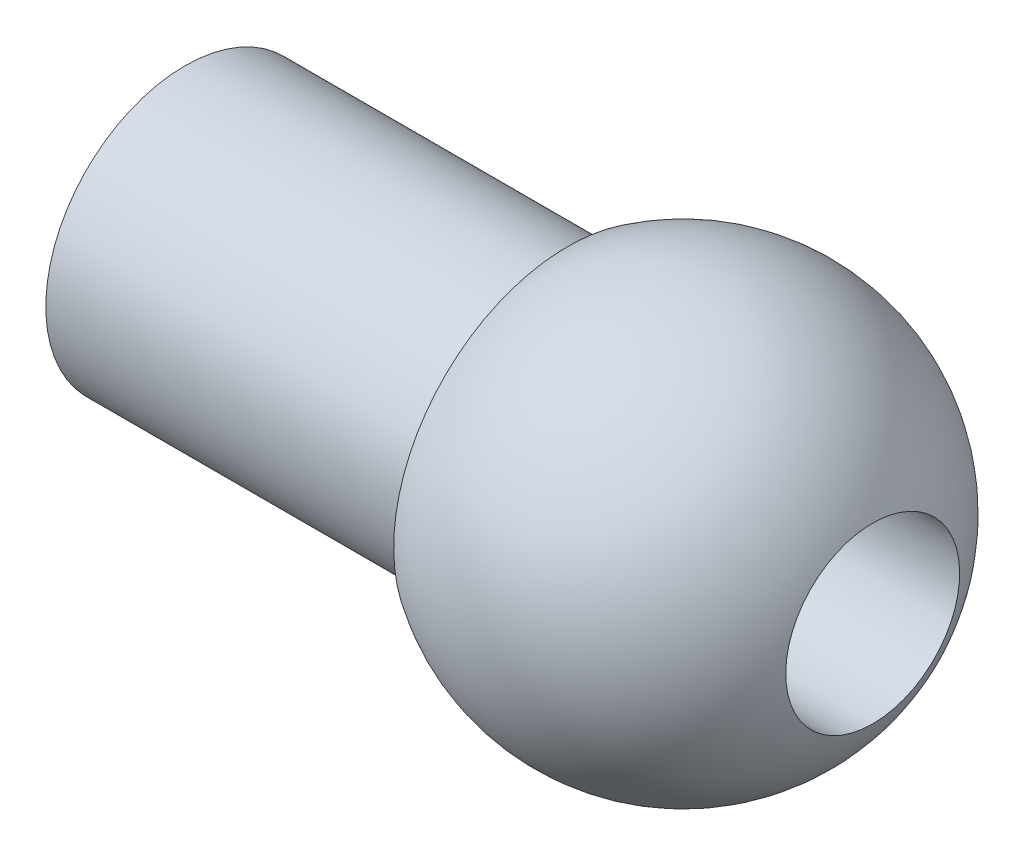
SolidWorks part; units mm, degrees
material "ABS"
ref_plane "Front Plane" through (0, 0, 0) normal (0, 0, 1) x (1, 0, 0)
ref_plane "Top Plane" through (0, 0, 0) normal (0, 1, 0) x (1, 0, 0)
ref_plane "Right Plane" through (0, 0, 0) normal (1, 0, 0) x (0, 0, -1)
sketch "Sketch1" plane through (0, 0, 0) normal (0, 0, 1) x (1, 0, 0)
  line L0 (-20.0169, 0) -> (20.0169, 0) construction
  line L1 (0, 0) -> (0, 4)
  line L2 (0, 4) -> (11, 4)
  line L3 (11, 4) -> (11, 5)
  line L4 (0, 0) -> (20.3166, 0)
  arc A0 (20.3166, 0) -> (11, 5) centre (14.3166, 0) ccw
  point P3 (0, 0)
  dimension "D4" = 6
  dimension "D1" = 4
  dimension "D2" = 11
  dimension "D3" = 1
revolve "Revolve1" add sketch "Sketch1" angle 360 about L0
sketch "Sketch2" plane through (0, 0, 0) normal (-1, 0, 0) x (0, 0, 1)
  circle A0 centre (0, 0) radius 2.5
  dimension "D1" = 5
extrude "Cut-Extrude1" cut sketch "Sketch2" against normal through all
